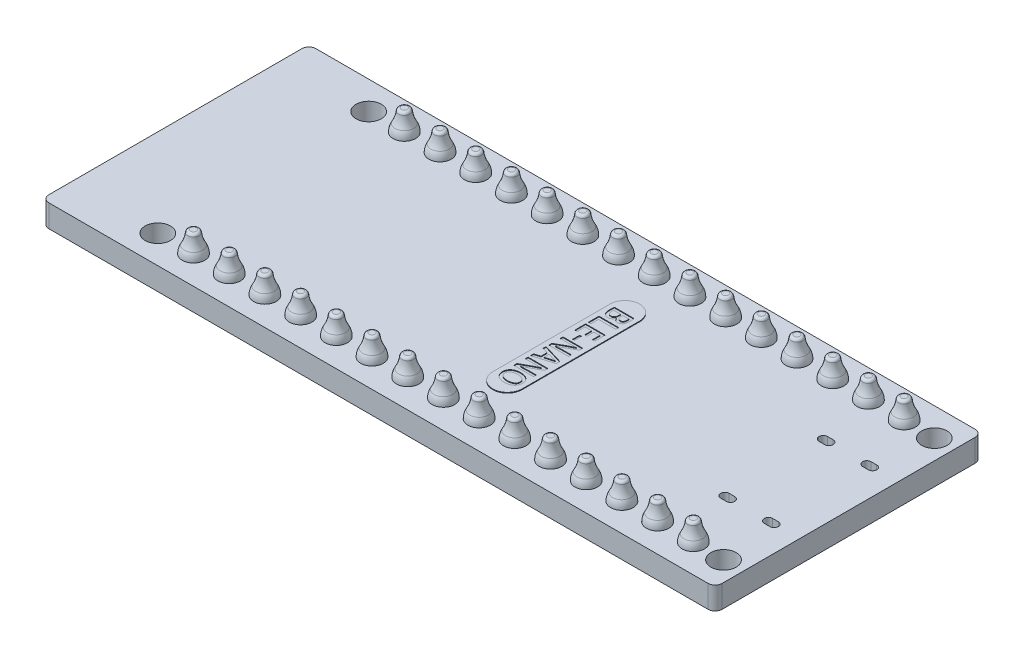
SolidWorks part; units mm, degrees
material "E-Glass Fiber"
ref_plane "Front Plane" through (0, 0, 0) normal (0, 0, 1) x (1, 0, 0)
ref_plane "Top Plane" through (0, 0, 0) normal (0, 1, 0) x (1, 0, 0)
ref_plane "Right Plane" through (0, 0, 0) normal (1, 0, 0) x (0, 0, -1)
sketch "Sketch1" plane through (0, 0, 0) normal (0, 1, 0) x (1, 0, 0)
  line L0 (0, 7.5) -> (-8.79, 7.5) construction
  line L1 (-8.79, 17) -> (39.11, 17)
  line L2 (-8.79, 17) -> (-8.79, -2)
  line L3 (-8.79, -2) -> (39.11, -2)
  line L4 (39.11, 17) -> (39.11, -2)
  line L5 (0, 0) -> (35.56, 0) construction
  line L6 (0, 0) -> (0, 15) construction
  line L7 (0, 15) -> (35.56, 15) construction
  line L8 (35.56, 0) -> (35.56, 15) construction
  line L10 (35.56, 7.5) -> (39.11, 7.5) construction
  dimension "D1" = 47.9
  dimension "D2" = 19
  dimension "D3" = 15
  dimension "D4" = 35.56
  dimension "D5" = 3.55
extrude "Boss-Extrude2" add sketch "Sketch1" along normal blind 1.6
sketch "Sketch2" plane through (0, 0, 0) normal (0, 1, 0) x (1, 0, 0)
  line L0 (0, -2.53) -> (0, 2.53) construction
  line L2 (-2.53, 0) -> (2.53, 0) construction
  circle A0 centre (0, 0) radius 0.45
  circle A1 centre (0, 15) radius 0.45
  dimension "D1" = 0.9
  dimension "D2" = 15
extrude "Cut-Extrude2" cut sketch "Sketch2" along normal blind 1.6
pattern_linear "LPattern1" count 15 spacing 2.54 along (1, 0, 0) of "Cut-Extrude2"
sketch "Sketch4" plane through (0, 0, 0) normal (0, 1, 0) x (1, 0, 0)
  line L0 (-0.88, 0) -> (0.88, 0) construction
  line L1 (0, -0.88) -> (0, 0.88) construction
  circle A0 centre (37.71, 15) radius 0.9
  circle A1 centre (37.71, 0) radius 0.9
  circle A2 centre (-2.54, 0) radius 0.9
  circle A3 centre (-2.54, 15) radius 0.9
  dimension "D3" = 1.8
  dimension "D1" = 40.25
  dimension "D2" = 2.54
  dimension "D4" = 15
  dimension "D5" = 15
extrude "Cut-Extrude5" cut sketch "Sketch4" along normal blind 1.6
sketch "Sketch5" plane through (0, 1.6, 0) normal (0, 1, 0) x (1, 0, 0)
  circle A0 centre (37.71, 15) radius 0.9
  circle A1 centre (37.71, 15) radius 1.275
  circle A2 centre (37.71, 15) radius 0.9 construction
  circle A3 centre (37.71, 0) radius 0.9
  circle A4 centre (37.71, 0) radius 0.9 construction
  circle A5 centre (37.71, 0) radius 1.275
  circle A6 centre (-2.54, 15) radius 0.9
  circle A7 centre (-2.54, 15) radius 1.275
  circle A8 centre (-2.54, 0) radius 0.9
  circle A9 centre (-2.54, 0) radius 1.275
  circle A10 centre (-2.54, 15) radius 0.9 construction
  circle A11 centre (-2.54, 0) radius 0.9 construction
  dimension "D1" = 2.55
extrude "Boss-Extrude3" [suppressed] add sketch "Sketch5" along normal blind 0.1
sketch "Sketch6" plane through (0, 0, 0) normal (1, 0, 0) x (0, 0, -1)
  line L0 (0, 1.6) -> (0.8, 1.6)
  line L1 (-1.5, 1.6) -> (16.5, 1.6) construction
  line L2 (0.2092, 3.1) -> (0, 3.1)
  line L3 (0, 1.54) -> (0, -1.54) construction
  line L4 (0, 3.1) -> (0, 1.6)
  line L5 (0, 1.3722) -> (0, 3.4408) construction
  arc A0 (0.8, 1.6) -> (0.6533, 2.1488) centre (-0.3, 1.6) ccw
  arc A1 (0.6533, 2.1488) -> (0.4083, 2.9187) centre (2.3, 3.0967) cw
  arc A2 (0.4083, 2.9187) -> (0.2092, 3.1) centre (0.2092, 2.9) ccw
  point P16 (0.4, 3.1)
  dimension "D4" = 1.1
  dimension "D5" = 1.9
  dimension "D6" = 0.2
  dimension "D1" = 1.5
  dimension "D2" = 0.8
  dimension "D3" = 1.6
revolve "Revolve1" add sketch "Sketch6" angle 360 about L5
pattern_linear "LPattern2" count 2 spacing 15 along (0, 0, -1) count 15 spacing 2.54 along (1, 0, 0) of "Revolve1"
ref_plane "Plane3" through (0, 0, -5.08) normal (0, 0, 1) x (1, 0, 0)
sketch "Sketch8" plane through (0, 0, 0) normal (0, -1, 0) x (1, 0, 0)
  circle A0 centre (37.71, 0) radius 0.9
  circle A1 centre (37.71, 0) radius 1.275
  circle A2 centre (37.71, -15) radius 1.275
  circle A3 centre (37.71, -15) radius 0.9
  circle A4 centre (37.71, -15) radius 0.9 construction
  circle A5 centre (37.71, 0) radius 0.9 construction
  circle A6 centre (-2.54, 0) radius 0.9
  circle A7 centre (-2.54, 0) radius 1.275
  circle A8 centre (-2.54, -15) radius 0.9
  circle A9 centre (-2.54, -15) radius 1.275
  circle A10 centre (-2.54, 0) radius 0.9 construction
  circle A11 centre (-2.54, -15) radius 0.9 construction
  dimension "D1" = 2.55
extrude "Boss-Extrude4" [suppressed] add sketch "Sketch8" along normal blind 0.1
sketch "Sketch9" plane through (0, 0, 0) normal (0, 1, 0) x (1, 0, 0)
  line L2 (36.91, 4) -> (37.31, 4) construction
  line L3 (36.91, 4.3) -> (37.31, 4.3)
  line L4 (36.91, 3.7) -> (37.31, 3.7)
  line L5 (-8.79, 7.5) -> (39.11, 7.5) construction
  line L6 (-8.79, 17) -> (-8.79, -2) construction
  line L7 (39.11, -2) -> (39.11, 17) construction
  line L8 (33.81, 4) -> (34.21, 4) construction
  line L9 (33.81, 4.3) -> (34.21, 4.3)
  line L10 (33.81, 3.7) -> (34.21, 3.7)
  line L11 (33.81, 11) -> (34.21, 11) construction
  line L12 (33.81, 11.3) -> (34.21, 11.3)
  line L13 (33.81, 10.7) -> (34.21, 10.7)
  line L14 (36.91, 11) -> (37.31, 11) construction
  line L15 (36.91, 11.3) -> (37.31, 11.3)
  line L16 (36.91, 10.7) -> (37.31, 10.7)
  arc A0 (36.91, 4.3) -> (36.91, 3.7) centre (36.91, 4) ccw
  arc A1 (37.31, 3.7) -> (37.31, 4.3) centre (37.31, 4) ccw
  arc A2 (33.81, 4.3) -> (33.81, 3.7) centre (33.81, 4) ccw
  arc A3 (34.21, 3.7) -> (34.21, 4.3) centre (34.21, 4) ccw
  arc A4 (33.81, 11.3) -> (33.81, 10.7) centre (33.81, 11) ccw
  arc A5 (34.21, 10.7) -> (34.21, 11.3) centre (34.21, 11) ccw
  arc A6 (36.91, 11.3) -> (36.91, 10.7) centre (36.91, 11) ccw
  arc A7 (37.31, 10.7) -> (37.31, 11.3) centre (37.31, 11) ccw
  point P2 (37.11, 4)
  point P7 (37.61, 4)
  point P20 (34.01, 4)
  point P27 (34.01, 11)
  point P34 (37.11, 11)
  dimension "D1" = 1
  dimension "D2" = 0.3
  dimension "D4" = 1.5
  dimension "D3" = 7
  dimension "D5" = 2
  dimension "D6" = 2
extrude "Cut-Extrude6" cut sketch "Sketch9" along normal blind 10
ref_plane "基准面1" through (0, 0, -7.5) normal (0, 0, 1) x (1, 0, 0)
ref_plane "基准面2" through (15.16, 0, 0) normal (1, 0, 0) x (0, 0, -1)
fillet "圆角1" radius 0.5 4 edges at (-8.79, 0.8, 2) (-8.79, 0.8, -17) (39.11, 0.8, 2) (39.11, 0.8, -17)
sketch "草图1" plane through (0, 1.6, 0) normal (0, 1, 0) x (1, 0, 0)
  line L0 (-8.79, 7.5) -> (39.11, 7.5) construction
  line L1 (-8.79, 16.5) -> (-8.79, -1.5) construction
  line L2 (39.11, -1.5) -> (39.11, 16.5) construction
  line L3 (19.01, 11.675) -> (19.01, 3.325) construction
  line L4 (20.06, 11.675) -> (20.06, 3.325)
  line L5 (17.96, 11.675) -> (17.96, 3.325)
  line L6 (17.96, 5.05) -> (17.96, 6.05) construction
  line L7 (18.34, 11.675) -> (18.34, 1.8933) construction
  arc A0 (20.06, 11.675) -> (17.96, 11.675) centre (19.01, 11.675) ccw
  arc A1 (17.96, 3.325) -> (20.06, 3.325) centre (19.01, 3.325) ccw
  point P8 (19.01, 7.5)
  dimension "D2" = 10.45
  dimension "D3" = 1.05
  dimension "D1" = 0
  dimension "D4" = 0.38
extrude "凸台-拉伸1" add sketch "草图1" along normal blind 0.05 separate body
sketch "草图2" plane through (0, 1.65, 0) normal (0, 1, 0) x (1, 0, 0)
  line L0 (18.31, 11.775) -> (18.31, 2.3397) construction
  line L1 (17.96, 11.675) -> (17.96, 3.325) construction
  arc A0 (20.06, 11.675) -> (17.96, 11.675) centre (19.01, 11.675) ccw construction
  text T0 "BLE-NANO" font "@Adobe 黑体 Std R" height 1.4
  dimension "D1" = 0.35
  dimension "D2" = 0.1
extrude "切除-拉伸1" cut sketch "草图2" against normal up to surface (0.05 mm away) up to face at (35.56, 1.6, -14.2)
sketch "草图3" plane through (0, 0, 0) normal (0, -1, 0) x (1, 0, 0)
  line L0 (22.21, -4) -> (28.26, -4)
  line L1 (4.21, -3.65) -> (9.31, -3.65)
  line L2 (4.21, -3.65) -> (4.21, -11.35)
  line L3 (4.21, -11.35) -> (9.31, -11.35)
  line L4 (9.31, -3.65) -> (9.31, -11.35)
  line L5 (14.01, -9.18) -> (15.26, -9.18)
  line L6 (14.01, -9.18) -> (14.01, -9.77)
  line L7 (14.01, -13.38) -> (21.81, -13.38)
  line L8 (21.81, -9.18) -> (21.81, -13.38)
  line L9 (15.26, -5.55) -> (17.86, -5.55)
  line L10 (15.26, -5.55) -> (15.26, -9.18)
  line L12 (17.86, -5.55) -> (17.86, -9.18)
  line L13 (11.36, -9.77) -> (14.01, -9.77)
  line L14 (11.36, -9.77) -> (11.36, -11.17)
  line L15 (11.36, -11.17) -> (14.01, -11.17)
  line L18 (35.91, -5.575) -> (35.91, -9.25)
  line L19 (35.91, -9.25) -> (38.21, -9.25)
  line L20 (38.21, -5.575) -> (38.21, -9.25)
  line L21 (-1.52, 1.52) -> (37.08, 1.52)
  line L22 (-1.52, 1.52) -> (-1.52, -1.52)
  line L23 (-1.52, -1.52) -> (37.08, -1.52)
  line L24 (37.08, 1.52) -> (37.08, -1.52)
  line L25 (-1.52, -13.48) -> (37.08, -13.48)
  line L26 (-1.52, -13.48) -> (-1.52, -16.52)
  line L27 (-1.52, -16.52) -> (37.08, -16.52)
  line L28 (37.08, -13.48) -> (37.08, -16.52)
  line L29 (28.26, -4) -> (28.26, -11)
  line L30 (28.26, -11) -> (24.41, -11)
  line L31 (33.79, 1.27) -> (32.25, 1.27) construction
  line L32 (34.79, -1.27) -> (36.33, -1.27) construction
  line L33 (36.83, -0.77) -> (36.83, 0.77) construction
  line L34 (-1.27, 0.77) -> (-1.27, -0.77) construction
  line L35 (14.01, -11.17) -> (14.01, -13.38)
  line L36 (17.86, -9.18) -> (21.81, -9.18)
  line L37 (-1.27, -14.23) -> (-1.27, -15.77) construction
  line L38 (0.77, -13.73) -> (-0.77, -13.73) construction
  line L39 (-0.77, -16.27) -> (0.77, -16.27) construction
  line L40 (36.83, -15.77) -> (36.83, -14.23) construction
  line L41 (37.91, -8.5) -> (37.91, -6.075) construction
  line L42 (36.21, -6.075) -> (36.21, -8.5) construction
  line L43 (37.91, -6.075) -> (36.21, -6.075) construction
  line L44 (36.11, -5.575) -> (36.11, -9.05)
  line L45 (36.11, -9.05) -> (38.01, -9.05)
  line L46 (38.01, -5.575) -> (38.01, -9.05)
  line L47 (-1.32, -1.32) -> (36.88, -1.32)
  line L48 (36.88, 1.32) -> (36.88, -1.32)
  line L49 (-1.32, 1.32) -> (36.88, 1.32)
  line L50 (-1.32, 1.32) -> (-1.32, -1.32)
  line L51 (-1.32, -13.68) -> (36.88, -13.68)
  line L52 (36.88, -13.68) -> (36.88, -16.32)
  line L53 (-1.32, -16.32) -> (36.88, -16.32)
  line L54 (-1.32, -13.68) -> (-1.32, -16.32)
  line L55 (35.91, -5.575) -> (36.11, -5.575)
  line L56 (38.01, -5.575) -> (38.21, -5.575)
  line L57 (24.51, -4.25) -> (28.01, -4.25) construction
  line L58 (28.01, -9) -> (28.01, -10.75) construction
  line L59 (28.01, -10.75) -> (24.51, -10.75) construction
  line L60 (24.51, -10.75) -> (24.51, -10.15) construction
  line L61 (22.11, -4.45) -> (22.11, -5.95) construction
  line L62 (13.31, -10.12) -> (12.01, -10.12) construction
  line L63 (13.31, -10.82) -> (12.01, -10.82) construction
  line L64 (11.61, -10.095) -> (11.61, -10.845) construction
  line L65 (17.61, -7.725) -> (17.61, -6.975) construction
  line L66 (17.21, -5.9) -> (15.91, -5.9) construction
  line L67 (15.51, -6.975) -> (15.51, -7.725) construction
  line L68 (13.71, -10.845) -> (13.71, -10.095) construction
  line L69 (-8.79, -7.5) -> (39.11, -7.5) construction
  line L70 (-8.79, -16.5) -> (-8.79, 1.5) construction
  line L71 (39.11, 1.5) -> (39.11, -16.5) construction
  line L72 (15.46, -5.75) -> (17.66, -5.75)
  line L73 (17.66, -5.75) -> (17.66, -9.38)
  line L74 (17.66, -9.38) -> (21.61, -9.38)
  line L75 (21.61, -9.38) -> (21.61, -13.18)
  line L76 (14.21, -13.18) -> (21.61, -13.18)
  line L77 (14.21, -10.97) -> (14.21, -13.18)
  line L78 (11.56, -10.97) -> (14.21, -10.97)
  line L79 (11.56, -9.97) -> (11.56, -10.97)
  line L80 (11.56, -9.97) -> (14.21, -9.97)
  line L81 (14.21, -9.38) -> (14.21, -9.97)
  line L82 (14.21, -9.38) -> (15.46, -9.38)
  line L83 (15.46, -5.75) -> (15.46, -9.38)
  line L84 (4.41, -3.85) -> (9.11, -3.85)
  line L85 (9.11, -3.85) -> (9.11, -11.15)
  line L86 (4.41, -11.15) -> (9.11, -11.15)
  line L87 (4.41, -3.85) -> (4.41, -11.15)
  line L88 (22.21, -4.2) -> (28.06, -4.2)
  line L89 (28.06, -4.2) -> (28.06, -10.8)
  line L90 (28.06, -10.8) -> (24.41, -10.8)
  line L91 (22.21, -4.2) -> (22.21, -4)
  line L92 (24.41, -11) -> (24.41, -10.8)
  point P36 (35.56, -1.27)
  point P99 (4.21, -7.5)
  dimension "D1" = 0.25
  dimension "D2" = 0.25
  dimension "D3" = 0.25
  dimension "D4" = 0.25
  dimension "D5" = 0.25
  dimension "D6" = 0.25
  dimension "D7" = 0.25
  dimension "D8" = 0.25
  dimension "D9" = 0.3
  dimension "D10" = 0.3
  dimension "D11" = 0.3
  dimension "D12" = 0.5
  dimension "D16" = 0.25
  dimension "D17" = 0.25
  dimension "D18" = 0.25
  dimension "D19" = 0.1
  dimension "D20" = 0.1
  dimension "D21" = 0.1
  dimension "D22" = 4.2
  dimension "D23" = 0.35
  dimension "D24" = 0.35
  dimension "D25" = 0.25
  dimension "D26" = 0.25
  dimension "D27" = 0.35
  dimension "D28" = 0.25
  dimension "D29" = 0.3
  dimension "D30" = 7.8
  dimension "D31" = 7.7
  dimension "D32" = 5.1
  dimension "D33" = 13
  dimension "D13" = 0.2
  dimension "D14" = 0.2
  dimension "D15" = 0.2
  dimension "D34" = 0.2
  dimension "D35" = 0.2
  dimension "D36" = 0.2
extrude "凸台-拉伸2" add sketch "草图3" along normal blind 0.05 separate body
sketch "草图4" plane through (0, 0, 0) normal (0, -1, 0) x (1, 0, 0)
  line L0 (17.66, -9.38) -> (17.66, -5.75) construction
  line L1 (15.46, -9.38) -> (17.66, -9.38)
  line L2 (15.46, -9.38) -> (15.46, -9.18)
  line L3 (15.46, -9.18) -> (17.66, -9.18)
  line L4 (17.66, -9.38) -> (17.66, -9.18)
  line L5 (11.56, -10.97) -> (14.21, -10.97) construction
  line L6 (14.21, -9.97) -> (14.01, -9.97)
  line L7 (14.21, -9.97) -> (14.21, -10.97)
  line L8 (14.21, -10.97) -> (14.01, -10.97)
  line L9 (14.01, -9.97) -> (14.01, -10.97)
  line L10 (14.01, -9.18) -> (14.01, -9.77) construction
  line L11 (15.26, -9.18) -> (14.01, -9.18) construction
extrude "凸台-拉伸3" add sketch "草图4" along normal blind 0.05 separate body
sketch "草图5" plane through (0, 0, 0) normal (0, -1, 0) x (1, 0, 0)
  line L0 (6.76, -3.85) -> (6.76, -11.15) construction
  line L1 (9.11, -3.85) -> (4.41, -3.85) construction
  line L2 (4.41, -11.15) -> (9.11, -11.15) construction
  line L3 (4.41, -7.5) -> (9.11, -7.5) construction
  line L4 (4.41, -3.85) -> (4.41, -11.15) construction
  line L5 (9.11, -11.15) -> (9.11, -3.85) construction
  line L6 (21.61, -11.28) -> (14.21, -11.28) construction
  line L7 (4.96, -4.2) -> (5.96, -4.2)
  line L8 (4.96, -4.2) -> (4.96, -5.2)
  line L9 (4.96, -5.2) -> (5.96, -5.2)
  line L10 (5.96, -4.2) -> (5.96, -5.2)
  line L11 (4.96, -4.2) -> (5.96, -5.2) construction
  line L12 (4.96, -5.2) -> (5.96, -4.2) construction
  line L13 (21.61, -13.18) -> (21.61, -9.38) construction
  line L14 (14.21, -10.97) -> (14.21, -13.18) construction
  line L15 (17.91, -13.18) -> (17.91, -9.38) construction
  line L16 (14.21, -13.18) -> (21.61, -13.18) construction
  line L17 (21.61, -9.38) -> (17.66, -9.38) construction
  line L18 (34.21, -11.3) -> (33.81, -11.3) construction
  line L19 (20.21, -9.48) -> (21.21, -9.48)
  line L20 (20.21, -9.48) -> (20.21, -10.48)
  line L21 (20.21, -10.48) -> (21.21, -10.48)
  line L22 (21.21, -9.48) -> (21.21, -10.48)
  line L23 (20.21, -9.48) -> (21.21, -10.48) construction
  line L24 (20.21, -10.48) -> (21.21, -9.48) construction
  line L25 (33.81, -10.7) -> (34.21, -10.7) construction
  line L26 (37.31, -11.3) -> (36.91, -11.3) construction
  line L27 (36.91, -10.7) -> (37.31, -10.7) construction
  line L28 (37.31, -4.3) -> (36.91, -4.3) construction
  line L29 (36.91, -3.7) -> (37.31, -3.7) construction
  line L30 (33.81, -3.7) -> (34.21, -3.7) construction
  line L31 (34.21, -4.3) -> (33.81, -4.3) construction
  line L32 (34.21, -11.3) -> (33.81, -11.3)
  line L33 (33.81, -10.7) -> (34.21, -10.7)
  line L34 (37.31, -11.3) -> (36.91, -11.3)
  line L35 (36.91, -10.7) -> (37.31, -10.7)
  line L36 (37.31, -4.3) -> (36.91, -4.3)
  line L37 (36.91, -3.7) -> (37.31, -3.7)
  line L38 (33.81, -3.7) -> (34.21, -3.7)
  line L39 (34.21, -4.3) -> (33.81, -4.3)
  line L40 (34.21, -4.55) -> (33.81, -4.55)
  line L41 (33.81, -3.45) -> (34.21, -3.45)
  line L42 (37.31, -4.55) -> (36.91, -4.55)
  line L43 (36.91, -3.45) -> (37.31, -3.45)
  line L44 (33.81, -10.45) -> (34.21, -10.45)
  line L45 (34.21, -11.55) -> (33.81, -11.55)
  line L46 (36.91, -10.45) -> (37.31, -10.45)
  line L47 (37.31, -11.55) -> (36.91, -11.55)
  circle A0 centre (5.46, -7.5) radius 0.45
  circle A1 centre (5.46, -10.3) radius 0.45
  circle A2 centre (8.06, -4.7) radius 0.45
  circle A3 centre (8.06, -7.5) radius 0.45
  circle A4 centre (8.06, -10.3) radius 0.45
  circle A5 centre (17.91, -9.98) radius 0.45
  circle A6 centre (15.11, -9.98) radius 0.45
  circle A7 centre (15.11, -12.58) radius 0.45
  circle A8 centre (17.91, -12.58) radius 0.45
  circle A9 centre (20.71, -12.58) radius 0.45
  arc A10 (33.81, -10.7) -> (33.81, -11.3) centre (33.81, -11) ccw construction
  arc A11 (34.21, -11.3) -> (34.21, -10.7) centre (34.21, -11) ccw construction
  arc A12 (36.91, -10.7) -> (36.91, -11.3) centre (36.91, -11) ccw construction
  arc A13 (37.31, -11.3) -> (37.31, -10.7) centre (37.31, -11) ccw construction
  arc A14 (37.31, -4.3) -> (37.31, -3.7) centre (37.31, -4) ccw construction
  arc A15 (36.91, -3.7) -> (36.91, -4.3) centre (36.91, -4) ccw construction
  arc A16 (34.21, -4.3) -> (34.21, -3.7) centre (34.21, -4) ccw construction
  arc A17 (33.81, -3.7) -> (33.81, -4.3) centre (33.81, -4) ccw construction
  arc A18 (33.81, -10.7) -> (33.81, -11.3) centre (33.81, -11) ccw
  arc A19 (34.21, -11.3) -> (34.21, -10.7) centre (34.21, -11) ccw
  arc A20 (36.91, -10.7) -> (36.91, -11.3) centre (36.91, -11) ccw
  arc A21 (37.31, -11.3) -> (37.31, -10.7) centre (37.31, -11) ccw
  arc A22 (37.31, -4.3) -> (37.31, -3.7) centre (37.31, -4) ccw
  arc A23 (36.91, -3.7) -> (36.91, -4.3) centre (36.91, -4) ccw
  arc A24 (34.21, -4.3) -> (34.21, -3.7) centre (34.21, -4) ccw
  arc A25 (33.81, -3.7) -> (33.81, -4.3) centre (33.81, -4) ccw
  arc A26 (33.81, -3.45) -> (33.81, -4.55) centre (33.81, -4) ccw
  arc A27 (34.21, -4.55) -> (34.21, -3.45) centre (34.21, -4) ccw
  arc A28 (36.91, -3.45) -> (36.91, -4.55) centre (36.91, -4) ccw
  arc A29 (37.31, -4.55) -> (37.31, -3.45) centre (37.31, -4) ccw
  arc A30 (34.21, -11.55) -> (34.21, -10.45) centre (34.21, -11) ccw
  arc A31 (33.81, -10.45) -> (33.81, -11.55) centre (33.81, -11) ccw
  arc A32 (37.31, -11.55) -> (37.31, -10.45) centre (37.31, -11) ccw
  arc A33 (36.91, -10.45) -> (36.91, -11.55) centre (36.91, -11) ccw
  point P12 (5.46, -4.7)
  point P39 (20.71, -9.98)
  point P54 (0, 0)
  point P55 (0, 0)
  point P56 (0, 0)
  point P57 (0, 0)
  point P58 (0, 0)
  point P59 (0, 0)
  dimension "D2" = 0.9
  dimension "D6" = 0.9
  dimension "D1" = 2.6
  dimension "D3" = 2.8
  dimension "D4" = 2.8
  dimension "D5" = 1
  dimension "D7" = 2.6
  dimension "D8" = 2.8
  dimension "D9" = 2.8
  dimension "D10" = 1
  dimension "D11" = 0.25
extrude "凸台-拉伸4" add sketch "草图5" along normal blind 0.05 separate body
